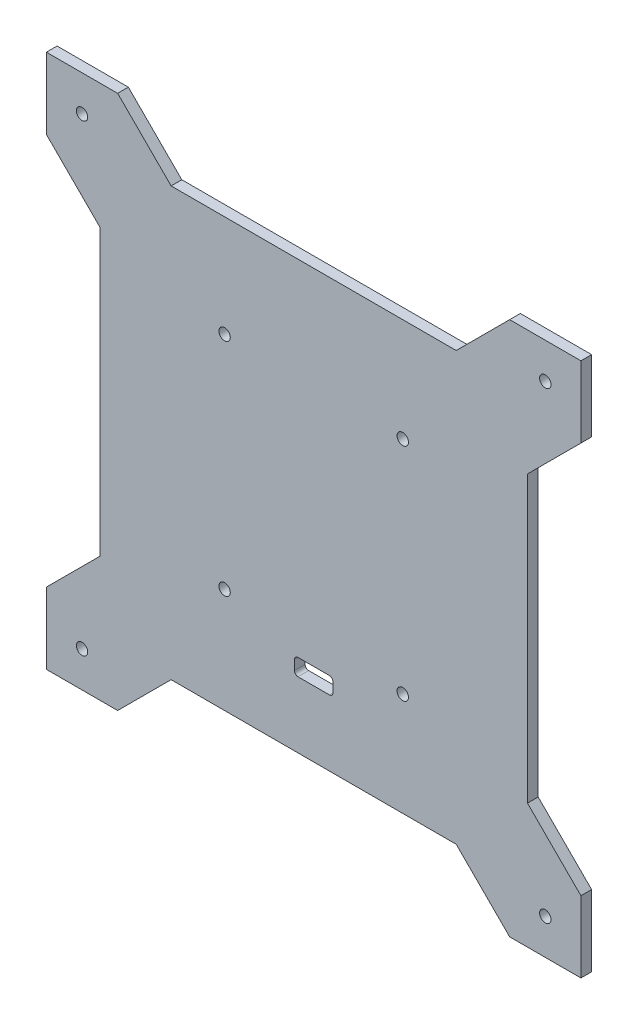
SolidWorks part; units mm, degrees
ref_plane "前视基准面" through (0, 0, 0) normal (0, 0, 1) x (1, 0, 0)
ref_plane "上视基准面" through (0, 0, 0) normal (0, 1, 0) x (1, 0, 0)
ref_plane "右视基准面" through (0, 0, 0) normal (1, 0, 0) x (0, 0, -1)
sketch "草图1" plane through (0, 0, 0) normal (0, 0, 1) x (1, 0, 0)
  line L1 (-75, -75) -> (75, -75)
  line L2 (-75, -75) -> (-75, 75)
  line L3 (-75, 75) -> (75, 75)
  line L4 (75, -75) -> (75, 75)
  line L5 (-75, -75) -> (75, 75) construction
  line L6 (-75, 75) -> (75, -75) construction
  circle A0 centre (-65, 65) radius 1.6
  circle A1 centre (65, 65) radius 1.6
  circle A2 centre (-65, -65) radius 1.6
  circle A3 centre (65, -65) radius 1.6
  point P0 (0, 0)
  dimension "D1" = 150
  dimension "D2" = 150
extrude "凸台-拉伸1" add sketch "草图1" along normal blind 3
sketch "草图2" plane through (0, 0, 3) normal (0, 0, 1) x (1, 0, 0)
  line L0 (75, -55) -> (75, 55)
  line L1 (60, 40) -> (75, 55)
  line L2 (-55, 75) -> (-40, 60)
  line L3 (75, 75) -> (-75, 75) construction
  line L4 (-40, 60) -> (40, 60)
  line L5 (40, 60) -> (55, 75)
  line L6 (0, 0) -> (0, -36.8899) construction
  line L7 (60, -40) -> (60, 40)
  line L8 (0, 0) -> (-75, -75) construction
  line L9 (-55, 75) -> (55, 75)
  line L10 (75, -55) -> (60, -40)
  line L11 (-75, -55) -> (-60, -40)
  line L12 (-60, -40) -> (-60, 40)
  line L13 (-60, 40) -> (-75, 55)
  line L14 (-75, -55) -> (-75, 55)
  line L15 (-55, -75) -> (55, -75)
  line L16 (40, -60) -> (55, -75)
  line L17 (-40, -60) -> (40, -60)
  line L18 (-55, -75) -> (-40, -60)
  circle A0 centre (-25, -30.5052) radius 1.6
  circle A1 centre (25, -31) radius 1.6
  circle A2 centre (25, 31) radius 1.6
  circle A3 centre (-25, 31.466) radius 1.6
  dimension "D1" = 3.2
  dimension "D2" = 110
  dimension "D3" = 45
  dimension "D4" = 45
  dimension "D5" = 15
  dimension "D6" = 20
extrude "切除-拉伸1" cut sketch "草图2" against normal blind 3
sketch "草图3" plane through (0, 0, 3) normal (0, 0, 1) x (1, 0, 0)
  line L0 (-5.4, -40.4873) -> (-5.4, -37.7873) construction
  line L1 (4.4, -41.4873) -> (-4.4, -41.4873) construction
  line L2 (5.4, -37.7873) -> (5.4, -40.4873) construction
  line L3 (-4.4, -36.7873) -> (4.4, -36.7873) construction
  line L4 (-5.4, -40.4873) -> (-5.4, -37.7873)
  line L5 (4.4, -41.4873) -> (-4.4, -41.4873)
  line L6 (5.4, -37.7873) -> (5.4, -40.4873)
  line L7 (-4.4, -36.7873) -> (4.4, -36.7873)
  arc A0 (-5.4, -40.4873) -> (-4.4, -41.4873) centre (-4.4, -40.4873) ccw construction
  arc A1 (-4.4, -36.7873) -> (-5.4, -37.7873) centre (-4.4, -37.7873) ccw construction
  arc A2 (4.4, -41.4873) -> (5.4, -40.4873) centre (4.4, -40.4873) ccw construction
  arc A3 (5.4, -37.7873) -> (4.4, -36.7873) centre (4.4, -37.7873) ccw construction
  arc A4 (-5.4, -40.4873) -> (-4.4, -41.4873) centre (-4.4, -40.4873) ccw
  arc A5 (-4.4, -36.7873) -> (-5.4, -37.7873) centre (-4.4, -37.7873) ccw
  arc A6 (4.4, -41.4873) -> (5.4, -40.4873) centre (4.4, -40.4873) ccw
  arc A7 (5.4, -37.7873) -> (4.4, -36.7873) centre (4.4, -37.7873) ccw
extrude "切除-拉伸2" cut sketch "草图3" against normal blind 3
